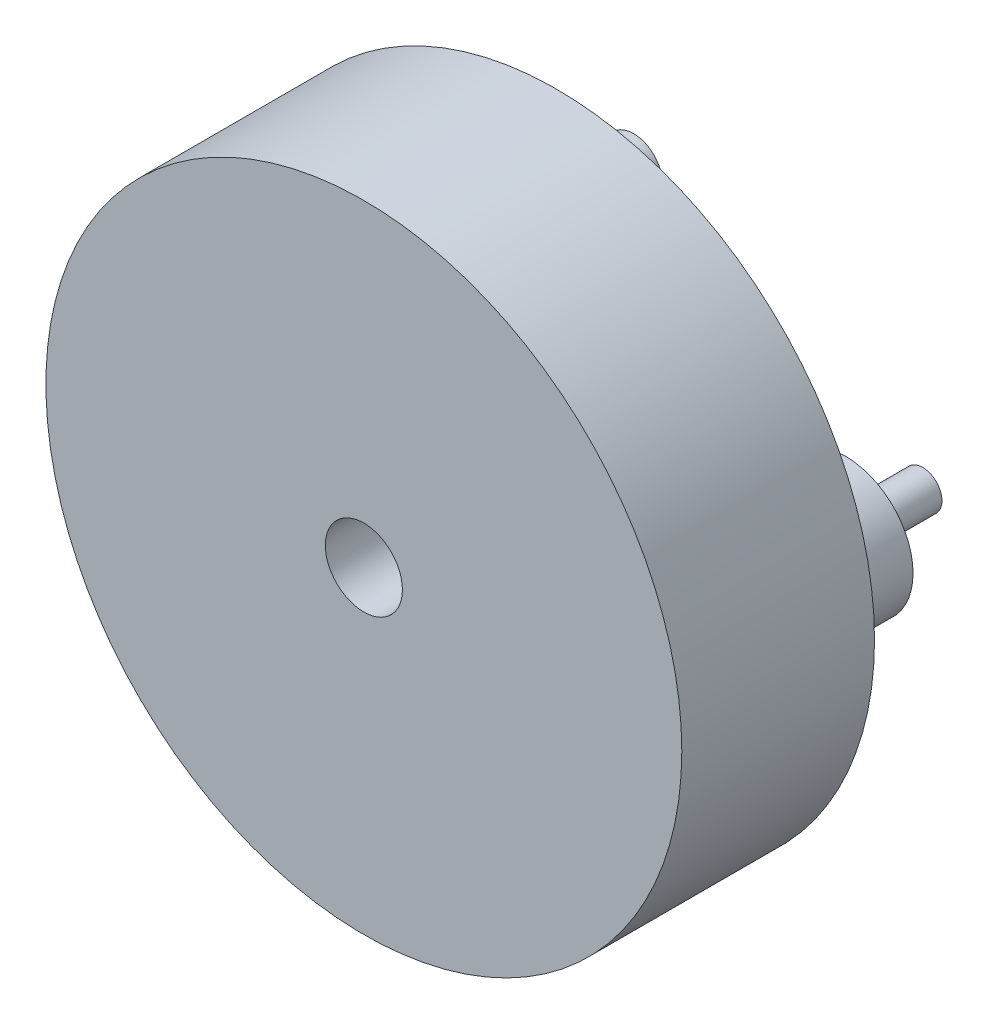
SolidWorks part; units mm, degrees
ref_plane "Front Plane" through (0, 0, 0) normal (0, 0, 1) x (1, 0, 0)
ref_plane "Top Plane" through (0, 0, 0) normal (0, 1, 0) x (1, 0, 0)
ref_plane "Right Plane" through (0, 0, 0) normal (1, 0, 0) x (0, 0, -1)
sketch "Sketch1" plane through (0, 0, 0) normal (0, 0, 1) x (1, 0, 0)
  circle A0 centre (0, 0) radius 8.25
  dimension "D1" = 16.5
extrude "Boss-Extrude1" add sketch "Sketch1" along normal blind 5
sketch "Sketch2" plane through (0, 0, 5) normal (0, 0, 1) x (1, 0, 0)
  circle A0 centre (0, 0) radius 1
  dimension "D1" = 2
extrude "Cut-Extrude1" cut sketch "Sketch2" against normal blind 2
sketch "Sketch3" plane through (0, 0, 0) normal (0, 0, -1) x (-1, 0, 0)
  line L0 (-5.5, 0) -> (5.5, 0) construction
  line L1 (0, -5.5) -> (0, 5.5) construction
  circle A0 centre (-5.5, 0) radius 1.75
  circle A1 centre (5.5, 0) radius 1.75
  circle A2 centre (0, 5.5) radius 0.75
  circle A3 centre (0, -5.5) radius 0.75
  dimension "D1" = 3.5
  dimension "D3" = 1.5
  dimension "D2" = 11
  dimension "D4" = 11
extrude "Boss-Extrude2" add sketch "Sketch3" along normal blind 2
sketch "Sketch4" plane through (0, 0, -2) normal (0, 0, -1) x (-1, 0, 0)
  circle A0 centre (-5.5, 0) radius 0.5
  circle A1 centre (5.5, 0) radius 0.5
  dimension "D1" = 1
extrude "Boss-Extrude3" add sketch "Sketch4" along normal blind 2
